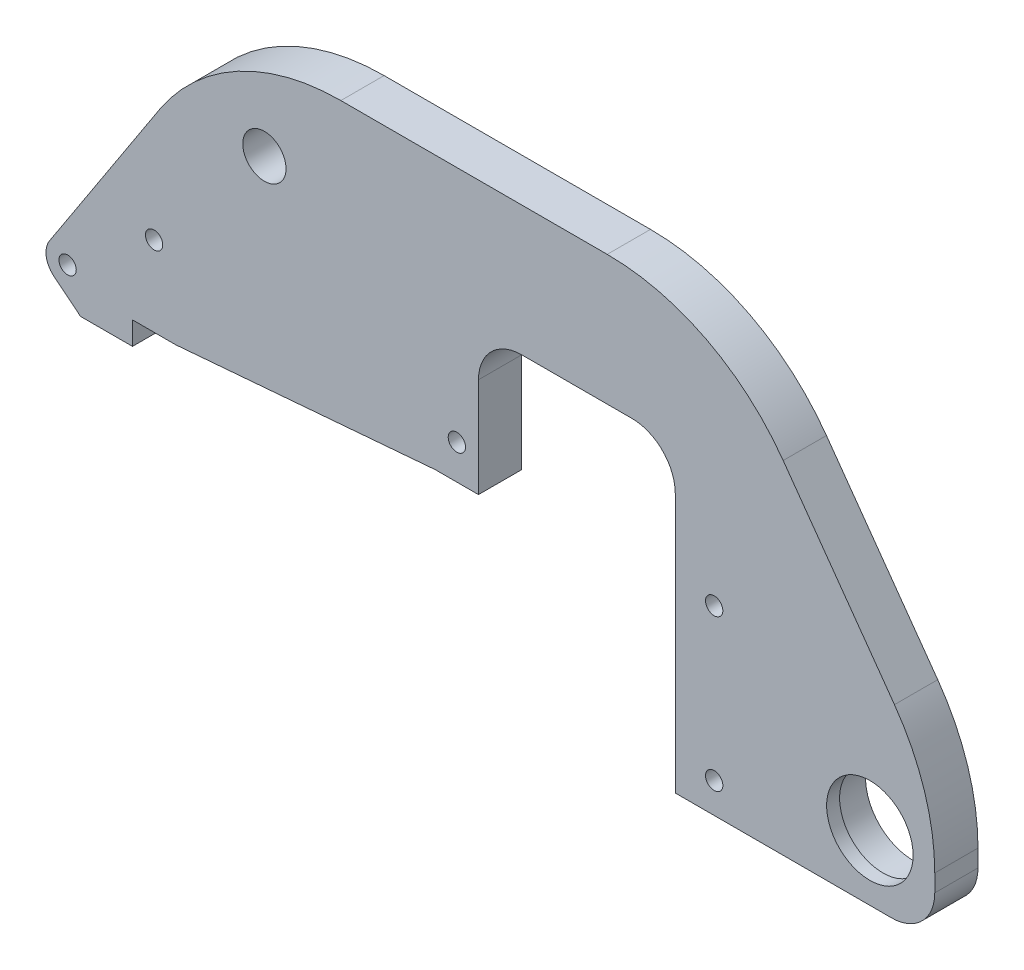
SolidWorks part; units mm, degrees
ref_plane "Plan de face" through (0, 0, 0) normal (0, 0, 1) x (1, 0, 0)
ref_plane "Plan de dessus" through (0, 0, 0) normal (0, 1, 0) x (1, 0, 0)
ref_plane "Plan de droite" through (0, 0, 0) normal (1, 0, 0) x (0, 0, -1)
sketch "Sketch1" plane through (0, 0, 0) normal (0, 0, 1) x (1, 0, 0)
  line L0 (-75, -18.32) -> (-75, -13)
  line L1 (-75, -13) -> (-65, -13)
  line L2 (50.5, -45) -> (50.5, 25)
  line L3 (5, -8) -> (-5, -8)
  line L4 (5, -8) -> (5, 8)
  line L5 (5, 8) -> (-5, 8)
  line L6 (-5, -8) -> (-5, 8)
  line L7 (5, -8) -> (-5, 8) construction
  line L8 (5, 8) -> (-5, -8) construction
  line L9 (5, 8) -> (5, 25)
  line L10 (5, 25) -> (50.5, 25)
  line L11 (50.5, -45) -> (76.1325, -45)
  line L12 (76.1325, -45) -> (110.5, -45)
  line L13 (110.5, -45) -> (110.5, -15)
  line L14 (110.5, -15) -> (60.5, 55)
  line L15 (60.5, 55) -> (-53.9096, 55)
  line L16 (-53.9096, 55) -> (-96.6586, -10.5573)
  line L17 (-96.6586, -10.5573) -> (-87.02, -18.32)
  line L18 (-87.02, -18.32) -> (-75, -18.32)
  line L19 (-65, -13) -> (-5, -8)
  line L20 (110.5, -30) -> (95.5, -30) construction
  line L21 (-90, -9.5) -> (-94.1882, -6.7689) construction
  line L22 (-90, -9.5) -> (-93.1362, -13.3941) construction
  circle A0 centre (-90, -9.5) radius 2
  circle A1 centre (-70, 5.5) radius 2
  circle A2 centre (0, 0) radius 2
  circle A3 centre (59.5, -3) radius 2
  circle A4 centre (59.5, -38) radius 2
  circle A5 centre (95.5, -30) radius 11
  point P15 (-88.2401, -18.32)
  point P33 (-97.8257, -9.5)
  point P35 (-53.9096, 55)
  dimension "D4" = 4
  dimension "D14" = 22
  dimension "D1" = 35
  dimension "D2" = 59.5
  dimension "D3" = 3
  dimension "D5" = 70
  dimension "D6" = 5.5
  dimension "D7" = 20
  dimension "D8" = 15
  dimension "D9" = 7
  dimension "D10" = 9
  dimension "D11" = 70
  dimension "D12" = 16
  dimension "D13" = 10
  dimension "D15" = 30
  dimension "D16" = 60
  dimension "D17" = 15
  dimension "D18" = 30
  dimension "D19" = 10
  dimension "D20" = 5
  dimension "D21" = 60
  dimension "D22" = 10
  dimension "D23" = 5.32
  dimension "D24" = 5
  dimension "D25" = 12.02
extrude "Boss-Extrude1" add sketch "Sketch1" along normal blind 10 contours L1 L19 L6 L5 L9 L10 L2 L11 L12 L13 L14 L15 L16 L17 L18 L0 A5 A4 A3 A1 A0 | L6 L3 L4 L5 A2
fillet "Fillet1" radius 10 3 edges at (110.5, -45, 5) (50.5, 25, 5) (5, 25, 5)
fillet "Fillet2" radius 50 3 edges at (110.5, -15, 5) (60.5, 55, 5) (-53.9096, 55, 5)
fillet "Fillet3" radius 5 1 edges at (-96.6586, -10.5573, 5)
sketch "Sketch2" plane through (0, 0, 10) normal (0, 0, 1) x (1, 0, 0)
  circle A0 centre (95.5, -30) radius 10
  circle A1 centre (95.5, -30) radius 11
  circle A2 centre (95.5, -30) radius 11 construction
  dimension "D1" = 1
extrude "Boss-Extrude2" add sketch "Sketch2" against normal blind 3
sketch "Sketch3" plane through (0, 0, 10) normal (0, 0, 1) x (1, 0, 0)
  circle A0 centre (-44.5, 35) radius 5
  circle A1 centre (95.5, -30) radius 10 construction
  dimension "D1" = 140
  dimension "D3" = 10
  dimension "D2" = 65
extrude "Cut-Extrude1" cut sketch "Sketch3" against normal through all both and the other way through all
